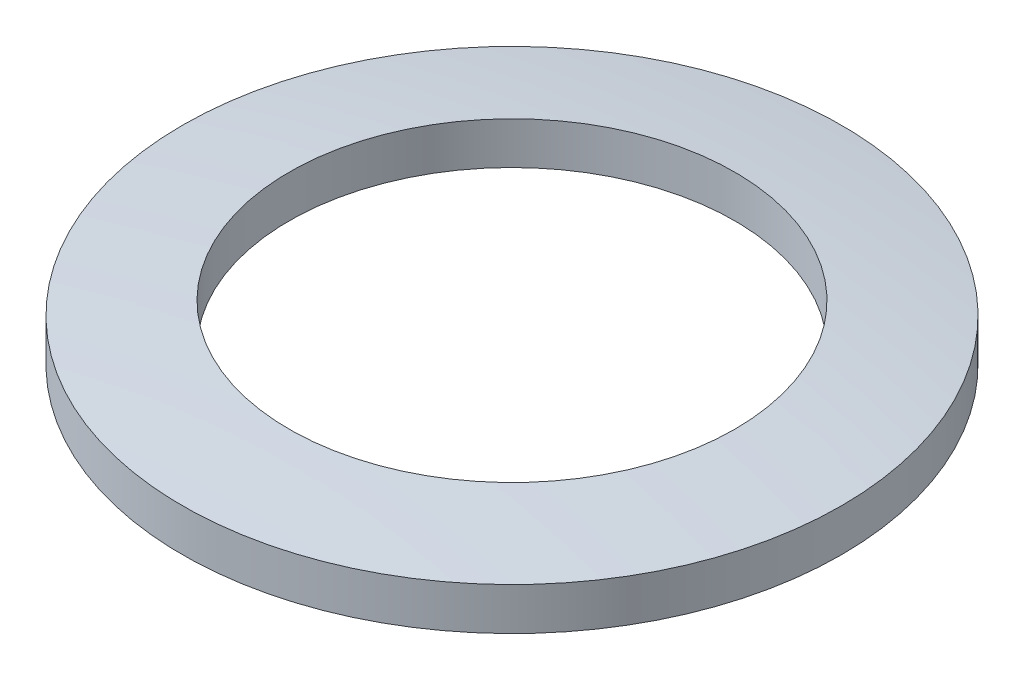
SolidWorks part; units mm, degrees
ref_plane "Front" through (0, 0, 0) normal (0, 0, 1) x (1, 0, 0)
ref_plane "Top" through (0, 0, 0) normal (0, 1, 0) x (1, 0, 0)
ref_plane "Right" through (0, 0, 0) normal (1, 0, 0) x (0, 0, -1)
sketch "Sketch1" plane through (0, 0, 0) normal (0, 0, 1) x (1, 0, 0)
  line L0 (26.51, 273.9704) -> (26.51, 268.9466)
  line L1 (0, 0) -> (26.51, 0) construction
  line L2 (0, 0) -> (0, 322.5334) construction
  line L3 (0, 322.5334) -> (26.51, 322.5334) construction
  line L4 (26.51, 0) -> (26.51, 322.5334) construction
  line L5 (0, 0) -> (39.22, 0) construction
  line L6 (0, 0) -> (0, 322.5334) construction
  line L7 (0, 322.5334) -> (39.22, 322.5334) construction
  line L8 (39.22, 0) -> (39.22, 322.5334) construction
  line L9 (39.22, 272.4415) -> (39.22, 267.389)
  arc A0 (39.22, 272.4415) -> (26.51, 273.9704) centre (0, 0) ccw
  arc A1 (39.22, 267.389) -> (26.51, 268.9466) centre (0, 0) ccw
  dimension "D1" = 550.5
  dimension "D2" = 540.5
  dimension "D3" = 26.51
  dimension "D4" = 39.22
revolve "Revolve1" add sketch "Sketch1" angle 360 about L2
